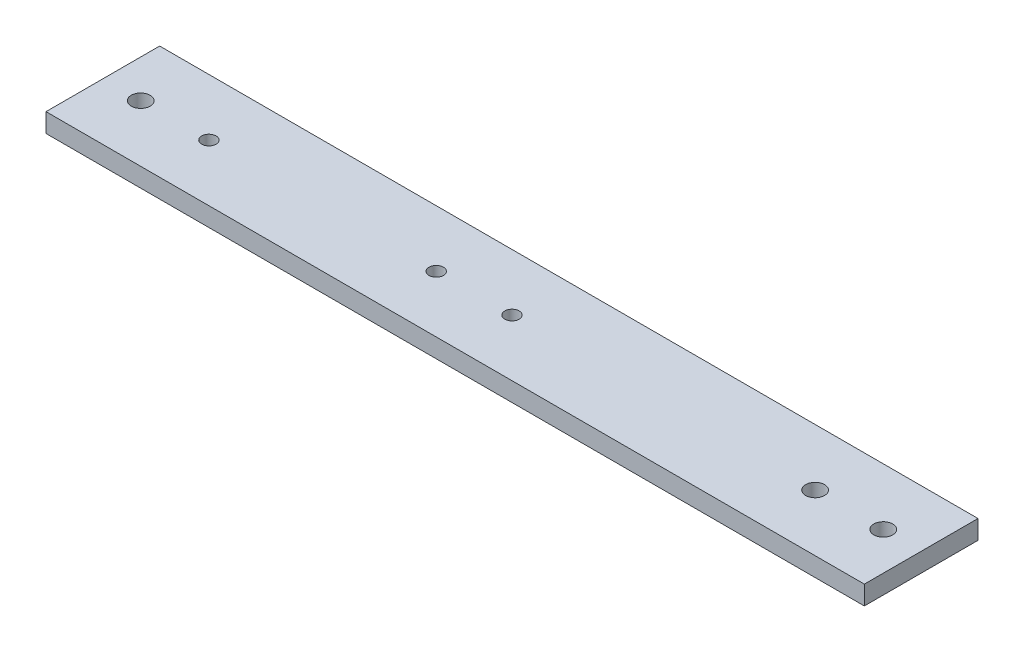
SolidWorks part; units mm, degrees
ref_plane "Front Plane" through (0, 0, 0) normal (0, 0, 1) x (1, 0, 0)
ref_plane "Top Plane" through (0, 0, 0) normal (0, 1, 0) x (1, 0, 0)
ref_plane "Right Plane" through (0, 0, 0) normal (1, 0, 0) x (0, 0, -1)
sketch "Sketch1" plane through (0, 0, 0) normal (0, 1, 0) x (1, 0, 0)
  line L0 (-137.16, 0) -> (137.16, 0) construction
  line L1 (-137.16, -19.05) -> (137.16, -19.05)
  line L2 (-137.16, -19.05) -> (-137.16, 19.05)
  line L3 (-137.16, 19.05) -> (137.16, 19.05)
  line L4 (137.16, -19.05) -> (137.16, 19.05)
  line L5 (-137.16, -19.05) -> (137.16, 19.05) construction
  line L6 (-137.16, 19.05) -> (137.16, -19.05) construction
  line L7 (-101.6, 0) -> (-137.16, 0) construction
  line L8 (101.6, 0) -> (137.16, 0) construction
  circle A0 centre (-124.46, 0) radius 3.175
  circle A1 centre (124.46, 0) radius 3.175
  circle A2 centre (-101.6, 0) radius 2.413
  circle A3 centre (-25.4, 0) radius 2.413
  circle A4 centre (0, 0) radius 2.413
  circle A5 centre (101.6, 0) radius 3.175
  point P0 (0, 0)
  dimension "D3" = 6.35
  dimension "D4" = 12.7
  dimension "D5" = 12.7
  dimension "D6" = 76.2
  dimension "D7" = 4.826
  dimension "D8" = 4.826
  dimension "D9" = 6.35
  dimension "D10" = 101.6
  dimension "D13" = 25.4
  dimension "D1" = 38.1
  dimension "D2" = 274.32
extrude "Boss-Extrude1" add sketch "Sketch1" along normal blind 6.35
